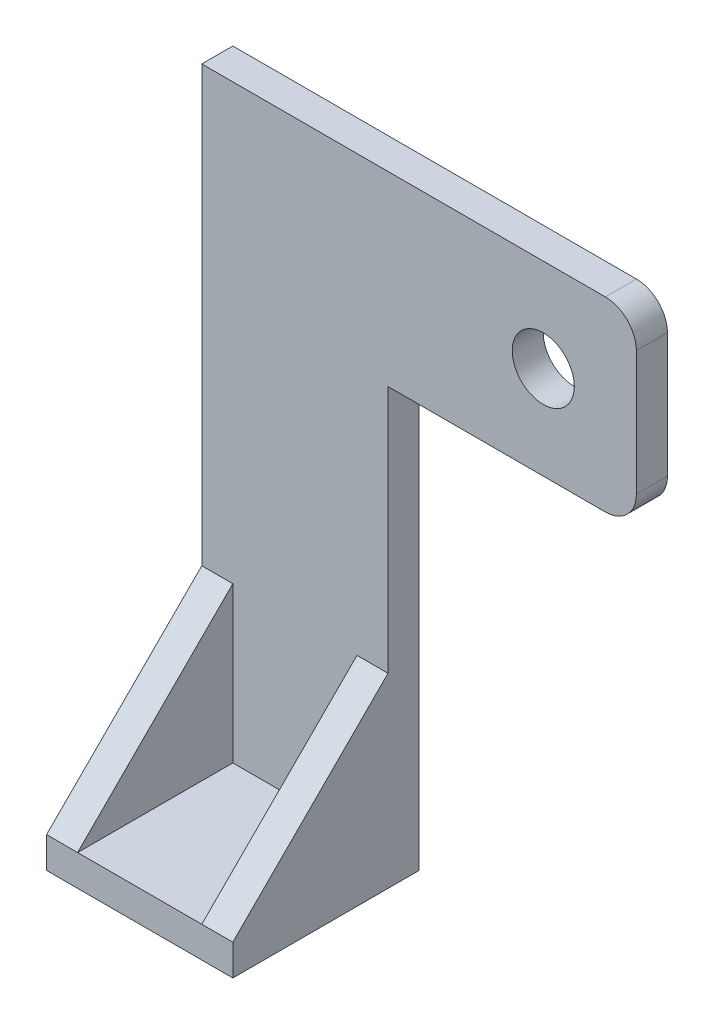
SolidWorks part; units mm, degrees
ref_plane "Front Plane" through (0, 0, 0) normal (0, 0, 1) x (1, 0, 0)
ref_plane "Top Plane" through (0, 0, 0) normal (0, 1, 0) x (1, 0, 0)
ref_plane "Right Plane" through (0, 0, 0) normal (1, 0, 0) x (0, 0, -1)
sketch "Sketch1" plane through (0, 0, 0) normal (0, 0, 1) x (1, 0, 0)
  line L0 (0, -15) -> (6.6093, -15) construction
  line L1 (5, 0) -> (70, 0)
  line L2 (0, -5) -> (0, -25)
  line L3 (5, -30) -> (40, -30)
  line L4 (70, 0) -> (70, -30)
  line L6 (70, -30) -> (70, -95)
  line L7 (70, -95) -> (40, -95)
  line L8 (40, -30) -> (40, -95)
  arc A1 (5, 0) -> (0, -5) centre (5, -5) ccw
  arc A2 (5, -30) -> (0, -25) centre (5, -25) cw
  dimension "D5" = 10
  dimension "D1" = 30
  dimension "D2" = 70
  dimension "D3" = 30
  dimension "D4" = 65
extrude "Boss-Extrude1" add sketch "Sketch1" along normal blind 5 contours L1 L4 L6 L7 L8 L3 A2 L2 A1
sketch "Sketch2" plane through (0, 0, 5) normal (0, 0, 1) x (1, 0, 0)
  line L0 (0, -5) -> (0, -25) construction
  line L1 (5, 0) -> (70, 0) construction
  circle A0 centre (15, -15) radius 5
  dimension "D1" = 10
  dimension "D2" = 15
  dimension "D3" = 15
extrude "Cut-Extrude1" cut sketch "Sketch2" against normal blind 10
sketch "Sketch3" plane through (0, -95, 0) normal (0, -1, 0) x (1, 0, 0)
  line L0 (70, 5) -> (70, 0) construction
  line L1 (40, 0) -> (70, 0)
  line L2 (40, 0) -> (40, 30)
  line L3 (40, 30) -> (70, 30)
  line L4 (70, 0) -> (70, 30)
  dimension "D1" = 30
extrude "Boss-Extrude2" add sketch "Sketch3" along normal blind 5
sketch "Sketch4" plane through (40, 0, 0) normal (-1, 0, 0) x (0, 0, 1)
  line L0 (5, -70) -> (30, -95)
  line L1 (5, -30) -> (5, -95) construction
  line L2 (30, -95) -> (5, -95)
  line L3 (5, -95) -> (5, -70)
extrude "Boss-Extrude3" add sketch "Sketch4" against normal blind 5
ref_plane "Plane1" through (55, 0, 0) normal (-1, 0, 0) x (0, 0, 1)
mirror "Mirror1" about plane through (55, 0, 0) normal (-1, 0, 0) of "Boss-Extrude3"
mirror "Mirror2" about plane through (55, 0, 0) normal (-1, 0, 0) of "Boss-Extrude1"
sketch "Sketch6" plane through (0, 0, 5) normal (0, 0, 1) x (1, 0, 0)
  line L0 (110, -5) -> (110, -25) construction
  line L1 (105, -30) -> (70, -30) construction
  circle A0 centre (95, -15) radius 5
  dimension "D1" = 10
  dimension "D2" = 15
  dimension "D3" = 15
extrude "Cut-Extrude2" cut sketch "Sketch6" against normal blind 5 contours A0
sketch "Sketch7" plane through (0, 0, 5) normal (0, 0, 1) x (1, 0, 0)
  line L1 (40, -30) -> (-6.5413, -30)
  line L2 (40, -30) -> (40, 4.0446)
  line L3 (40, 4.0446) -> (-6.5413, 4.0446)
  line L4 (-6.5413, -30) -> (-6.5413, 4.0446)
extrude "Cut-Extrude3" cut sketch "Sketch7" against normal blind 5
